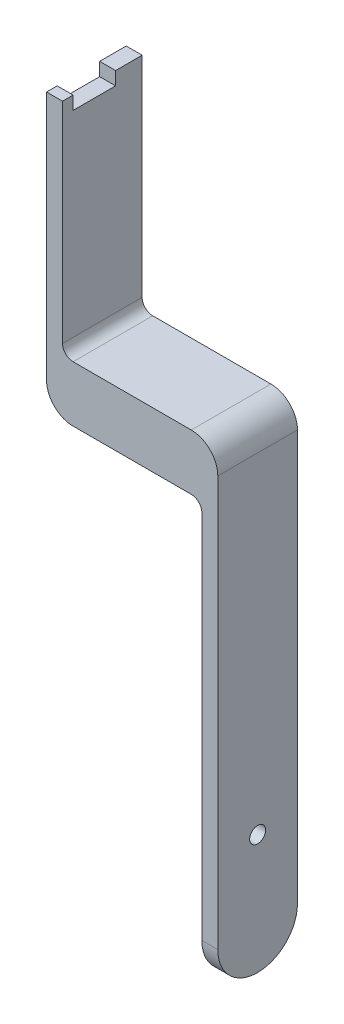
SolidWorks part; units mm, degrees
ref_plane "Front Plane" through (0, 0, 0) normal (0, 0, 1) x (1, 0, 0)
ref_plane "Top Plane" through (0, 0, 0) normal (0, 1, 0) x (1, 0, 0)
ref_plane "Right Plane" through (0, 0, 0) normal (1, 0, 0) x (0, 0, -1)
ref_plane "Plane1" through (72.2511, 0, 0) normal (1, 0, 0) x (0, 0, -1)
sketch "Sketch1" plane through (72.2511, 0, 0) normal (1, 0, 0) x (0, 0, -1)
  line L0 (105.5306, -79.2511) -> (105.5306, 44.5022)
  line L1 (105.5306, 44.5022) -> (90.5306, 44.5022)
  line L2 (90.5306, 44.5022) -> (90.5306, -79.2511)
  arc A0 (90.5306, -79.2511) -> (105.5306, -79.2511) centre (98.0306, -79.2511) ccw
extrude "Boss-Extrude1" add sketch "Sketch1" against normal blind 32.2511
sketch "Sketch2" plane through (0, 0, -105.5306) normal (0, 0, -1) x (-1, 0, 0)
  line L0 (-72.2511, 44.5022) -> (-72.2511, 3)
  line L1 (-72.2511, 3) -> (-43, 3)
  line L2 (-43, 3) -> (-43, 44.5022)
  line L3 (-43, 44.5022) -> (-72.2511, 44.5022)
extrude "Cut-Extrude1" cut sketch "Sketch2" against normal through all
sketch "Sketch3" plane through (0, 0, -105.5306) normal (0, 0, -1) x (-1, 0, 0)
  line L0 (-40, -7.5) -> (-69.2511, -7.5)
  line L1 (-69.2511, -7.5) -> (-69.2511, -86.7511)
  line L2 (-69.2511, -86.7511) -> (-40, -86.7511)
  line L3 (-40, -86.7511) -> (-40, -7.5)
  line L4 (-72.2511, -86.7511) -> (-40, -86.7511) construction
extrude "Cut-Extrude2" cut sketch "Sketch3" against normal through all
sketch "Sketch4" plane through (40, 0, 0) normal (-1, 0, 0) x (0, 0, 1)
  line L0 (-92.5306, 44.5022) -> (-100.5306, 44.5022)
  line L1 (-100.5306, 44.5022) -> (-100.5306, 42.0022)
  line L2 (-100.5306, 42.0022) -> (-92.5306, 42.0022)
  line L3 (-92.5306, 42.0022) -> (-92.5306, 44.5022)
extrude "Cut-Extrude3" cut sketch "Sketch4" against normal through all
hole_wizard "Ø3.0 (3) Diameter Hole1" positions "Sketch6" profile "Sketch5" hole size "Ø3.0" standard "ANSI Metric"
sketch "Sketch6" plane through (69.2511, 0, 0) normal (-1, 0, 0) x (0, 0, 1)
  point P0 (-98.0306, -64.2511)
sketch "Sketch5" plane through (69.2511, -64.2511, -98.0306) normal (0, 1, 0) x (0, 0, 1)
  line L0 (0, 0) -> (0, 3)
  line L1 (0, 3) -> (1.5, 3)
  line L2 (1.5, 3) -> (1.5, 0)
  line L5 (1.5, 0) -> (0, 0)
  line L11 (0, -6.35) -> (0, 107.95) construction
  dimension "Thru Hole Dia." = 3
  dimension "Thru Hole Depth" = 3
fillet "Fillet1" radius 2 2 edges at (43, 3, -98.0306) (69.2511, -7.5, -98.0306)
fillet "Fillet2" radius 5 2 edges at (40, -7.5, -98.0306) (72.2511, 3, -98.0306)
